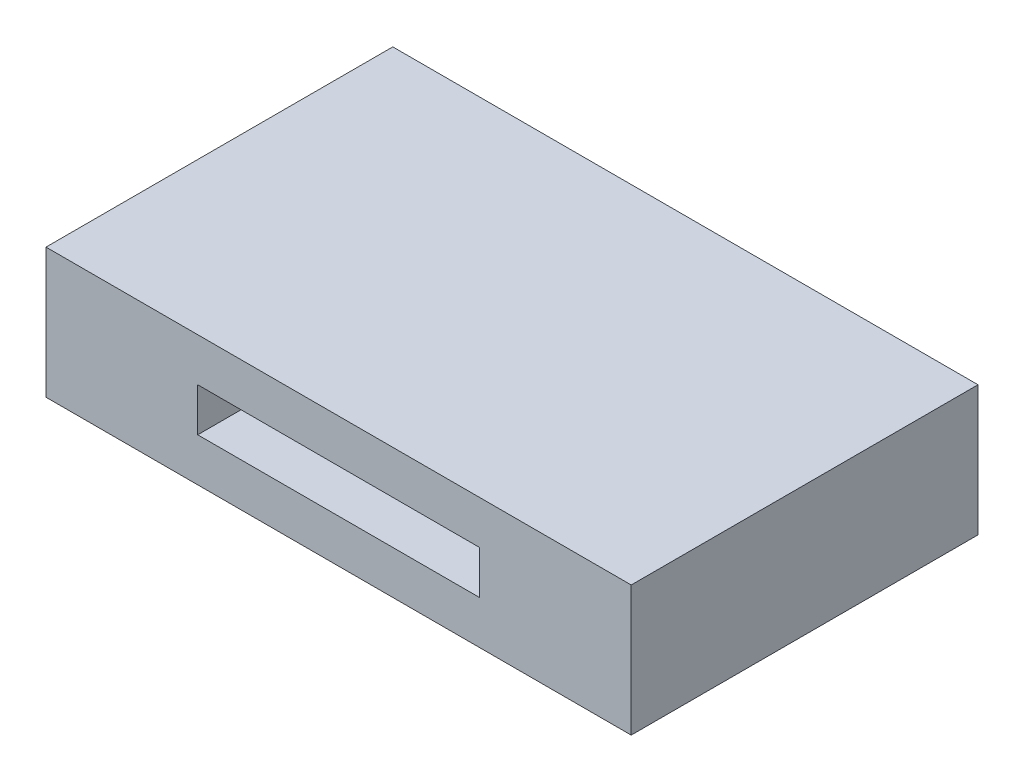
SolidWorks part; units mm, degrees
ref_plane "Front Plane" through (0, 0, 0) normal (0, 0, 1) x (1, 0, 0)
ref_plane "Top Plane" through (0, 0, 0) normal (0, 1, 0) x (1, 0, 0)
ref_plane "Right Plane" through (0, 0, 0) normal (1, 0, 0) x (0, 0, -1)
sketch "Sketch1" plane through (0, 0, 0) normal (0, 0, 1) x (1, 0, 0)
  line L1 (-6.5, -1) -> (6.5, -1)
  line L2 (-6.5, -1) -> (-6.5, 1)
  line L3 (-6.5, 1) -> (6.5, 1)
  line L4 (6.5, -1) -> (6.5, 1)
  line L5 (-6.5, -1) -> (6.5, 1) construction
  line L6 (-6.5, 1) -> (6.5, -1) construction
  line L7 (-13.5, -3) -> (13.5, -3)
  line L8 (-13.5, -3) -> (-13.5, 3)
  line L9 (-13.5, 3) -> (13.5, 3)
  line L10 (13.5, -3) -> (13.5, 3)
  line L11 (-13.5, -3) -> (13.5, 3) construction
  line L12 (-13.5, 3) -> (13.5, -3) construction
  point P0 (0, 0)
  point P6 (0, 0)
  dimension "D1" = 13
  dimension "D2" = 2
  dimension "D3" = 27
  dimension "D4" = 6
extrude "Boss-Extrude1" add sketch "Sketch1" along normal blind 16
